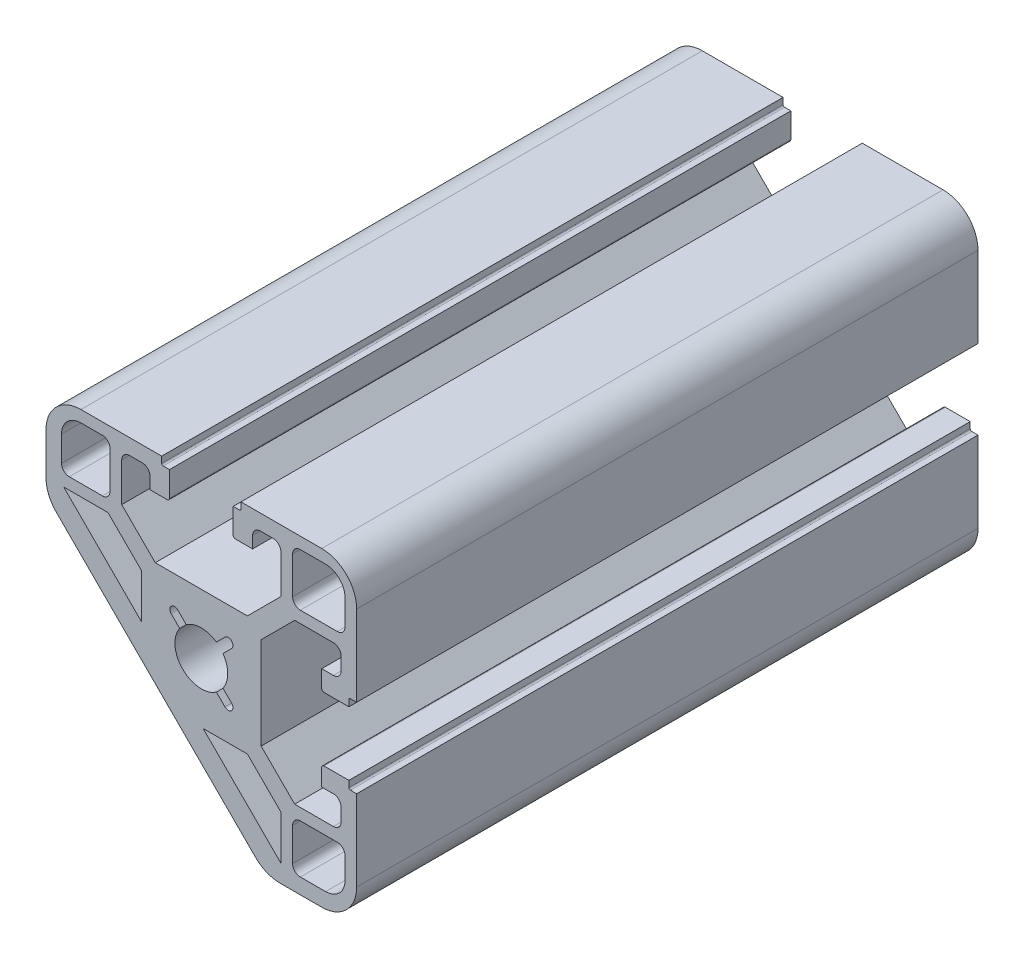
SolidWorks part; units mm, degrees
ref_plane "前视基准面" through (0, 0, 0) normal (0, 0, 1) x (1, 0, 0)
ref_plane "上视基准面" through (0, 0, 0) normal (0, 1, 0) x (1, 0, 0)
ref_plane "右视基准面" through (0, 0, 0) normal (1, 0, 0) x (0, 0, -1)
sketch "草图1" plane through (0, 0, 0) normal (0, 0, 1) x (1, 0, 0)
  line L0 (2339.1839, 210.4729) -> (2328.7839, 210.4729)
  line L1 (2324.2839, 205.9729) -> (2324.2839, 200.6211)
  line L2 (2325.6019, 197.4392) -> (2351.2501, 171.7909)
  line L3 (2354.4321, 170.4729) -> (2359.7839, 170.4729)
  line L4 (2364.2839, 174.9729) -> (2364.2839, 185.3729)
  line L5 (2337.6839, 205.9729) -> (2337.6839, 207.4729)
  line L6 (2336.6839, 208.4729) -> (2335.0339, 208.4729)
  line L7 (2334.0339, 207.4729) -> (2334.0339, 202.4907)
  line L8 (2340.1839, 209.4729) -> (2339.3839, 209.4729)
  line L9 (2339.1839, 209.6729) -> (2339.1839, 210.4729)
  line L10 (2340.1839, 209.4729) -> (2340.1839, 206.2729)
  line L11 (2339.8839, 205.9729) -> (2337.6839, 205.9729)
  line L12 (2338.3516, 198.1729) -> (2350.2161, 198.1729)
  line L13 (2326.2799, 206.4769) -> (2326.2799, 203.2229)
  line L14 (2327.2799, 202.2229) -> (2331.5339, 202.2229)
  line L15 (2332.5339, 203.2229) -> (2332.5339, 207.9769)
  line L16 (2331.5339, 208.9769) -> (2328.7799, 208.9769)
  line L17 (2344.5108, 182.7729) -> (2350.2161, 182.7729)
  line L18 (2336.5839, 196.4051) -> (2336.5839, 190.6998)
  line L19 (2351.9839, 184.5407) -> (2351.9839, 196.4051)
  line L20 (2350.2161, 198.1729) -> (2338.3516, 198.1729)
  line L21 (2332.2661, 200.7229) -> (2336.5839, 196.4051)
  line L22 (2334.0339, 202.4907) -> (2338.3516, 198.1729)
  line L23 (2349.3839, 210.4729) -> (2359.7839, 210.4729)
  line L24 (2364.2839, 205.9729) -> (2364.2839, 195.5729)
  line L25 (2350.8839, 205.9729) -> (2350.8839, 207.4729)
  line L26 (2351.8839, 208.4729) -> (2353.5339, 208.4729)
  line L27 (2354.5339, 207.4729) -> (2354.5339, 202.4907)
  line L28 (2348.3839, 209.4729) -> (2349.1839, 209.4729)
  line L29 (2349.3839, 209.6729) -> (2349.3839, 210.4729)
  line L30 (2364.2839, 195.5729) -> (2363.4839, 195.5729)
  line L31 (2363.2839, 195.3729) -> (2363.2839, 194.5729)
  line L32 (2359.7839, 197.0729) -> (2359.7839, 194.8729)
  line L33 (2360.0839, 194.5729) -> (2363.2839, 194.5729)
  line L34 (2348.3839, 209.4729) -> (2348.3839, 206.2729)
  line L35 (2348.6839, 205.9729) -> (2350.8839, 205.9729)
  line L36 (2362.7879, 206.4769) -> (2362.7879, 203.2229)
  line L37 (2361.7879, 202.2229) -> (2357.0339, 202.2229)
  line L38 (2356.0339, 203.2229) -> (2356.0339, 207.9769)
  line L39 (2357.0339, 208.9769) -> (2360.2879, 208.9769)
  line L40 (2356.3016, 200.7229) -> (2351.9839, 196.4051)
  line L41 (2354.5339, 202.4907) -> (2350.2161, 198.1729)
  line L42 (2359.7839, 197.0729) -> (2361.2839, 197.0729)
  line L43 (2362.2839, 198.0729) -> (2362.2839, 199.7229)
  line L44 (2361.2839, 200.7229) -> (2356.3016, 200.7229)
  line L45 (2364.2839, 185.3729) -> (2363.4839, 185.3729)
  line L46 (2363.2839, 185.5729) -> (2363.2839, 186.3729)
  line L47 (2359.7839, 183.8729) -> (2359.7839, 186.0729)
  line L48 (2360.0839, 186.3729) -> (2363.2839, 186.3729)
  line L49 (2348.3839, 174.6572) -> (2348.3839, 174.6729)
  line L50 (2362.7879, 174.9689) -> (2362.7879, 177.7229)
  line L51 (2361.7879, 178.7229) -> (2357.0339, 178.7229)
  line L52 (2356.0339, 177.7229) -> (2356.0339, 173.4689)
  line L53 (2357.0339, 172.4689) -> (2360.2879, 172.4689)
  line L54 (2356.3016, 180.2229) -> (2351.9839, 184.5407)
  line L55 (2354.5339, 178.4551) -> (2350.2161, 182.7729)
  line L56 (2359.7839, 183.8729) -> (2361.2839, 183.8729)
  line L57 (2362.2839, 182.8729) -> (2362.2839, 181.2229)
  line L58 (2361.2839, 180.2229) -> (2356.3016, 180.2229)
  line L59 (2326.5608, 200.7229) -> (2336.5839, 190.6998)
  line L60 (2344.5108, 182.7729) -> (2354.5339, 172.7498)
  line L61 (2332.2661, 200.7229) -> (2326.5608, 200.7229)
  line L62 (2354.5339, 178.4551) -> (2354.5339, 172.7498)
  line L63 (2347.3244, 194.362) -> (2346.226, 193.2636)
  line L64 (2348.1729, 193.5135) -> (2347.0746, 192.4151)
  line L65 (2341.2433, 194.362) -> (2342.3417, 193.2636)
  line L66 (2340.3948, 193.5135) -> (2341.4932, 192.4151)
  line L67 (2347.3244, 186.5838) -> (2346.226, 187.6822)
  line L68 (2348.1729, 187.4324) -> (2347.0746, 188.5307)
  arc A0 (2328.7839, 210.4729) -> (2324.2839, 205.9729) centre (2328.7839, 205.9729) ccw
  arc A1 (2324.2839, 200.6211) -> (2325.6019, 197.4392) centre (2328.7839, 200.6211) ccw
  arc A2 (2351.2501, 171.7909) -> (2354.4321, 170.4729) centre (2354.4321, 174.9729) ccw
  arc A3 (2359.7839, 170.4729) -> (2364.2839, 174.9729) centre (2359.7839, 174.9729) ccw
  arc A4 (2337.6839, 207.4729) -> (2336.6839, 208.4729) centre (2336.6839, 207.4729) ccw
  arc A5 (2335.0339, 208.4729) -> (2334.0339, 207.4729) centre (2335.0339, 207.4729) ccw
  arc A6 (2339.1839, 209.6729) -> (2339.3839, 209.4729) centre (2339.3839, 209.6729) ccw
  arc A7 (2339.8839, 205.9729) -> (2340.1839, 206.2729) centre (2339.8839, 206.2729) ccw
  arc A8 (2346.226, 193.2636) -> (2342.3417, 193.2636) centre (2344.2839, 190.4729) ccw
  arc A9 (2341.4932, 192.4151) -> (2346.226, 187.6822) centre (2344.2839, 190.4729) ccw
  arc A10 (2347.0746, 188.5307) -> (2347.0746, 192.4151) centre (2344.2839, 190.4729) ccw
  arc A11 (2326.2799, 203.2229) -> (2327.2799, 202.2229) centre (2327.2799, 203.2229) ccw
  arc A12 (2332.5339, 207.9769) -> (2331.5339, 208.9769) centre (2331.5339, 207.9769) ccw
  arc A13 (2331.5339, 202.2229) -> (2332.5339, 203.2229) centre (2331.5339, 203.2229) ccw
  arc A14 (2328.7799, 208.9769) -> (2326.2799, 206.4769) centre (2328.7799, 206.4769) ccw
  arc A15 (2364.2839, 205.9729) -> (2359.7839, 210.4729) centre (2359.7839, 205.9729) ccw
  arc A16 (2351.8839, 208.4729) -> (2350.8839, 207.4729) centre (2351.8839, 207.4729) ccw
  arc A17 (2354.5339, 207.4729) -> (2353.5339, 208.4729) centre (2353.5339, 207.4729) ccw
  arc A18 (2349.1839, 209.4729) -> (2349.3839, 209.6729) centre (2349.1839, 209.6729) ccw
  arc A19 (2363.4839, 195.5729) -> (2363.2839, 195.3729) centre (2363.4839, 195.3729) ccw
  arc A20 (2359.7839, 194.8729) -> (2360.0839, 194.5729) centre (2360.0839, 194.8729) ccw
  arc A21 (2348.3839, 206.2729) -> (2348.6839, 205.9729) centre (2348.6839, 206.2729) ccw
  arc A22 (2361.7879, 202.2229) -> (2362.7879, 203.2229) centre (2361.7879, 203.2229) ccw
  arc A23 (2357.0339, 208.9769) -> (2356.0339, 207.9769) centre (2357.0339, 207.9769) ccw
  arc A24 (2356.0339, 203.2229) -> (2357.0339, 202.2229) centre (2357.0339, 203.2229) ccw
  arc A25 (2362.7879, 206.4769) -> (2360.2879, 208.9769) centre (2360.2879, 206.4769) ccw
  arc A26 (2361.2839, 197.0729) -> (2362.2839, 198.0729) centre (2361.2839, 198.0729) ccw
  arc A27 (2362.2839, 199.7229) -> (2361.2839, 200.7229) centre (2361.2839, 199.7229) ccw
  arc A28 (2363.2839, 185.5729) -> (2363.4839, 185.3729) centre (2363.4839, 185.5729) ccw
  arc A29 (2360.0839, 186.3729) -> (2359.7839, 186.0729) centre (2360.0839, 186.0729) ccw
  arc A30 (2362.7879, 177.7229) -> (2361.7879, 178.7229) centre (2361.7879, 177.7229) ccw
  arc A31 (2356.0339, 173.4689) -> (2357.0339, 172.4689) centre (2357.0339, 173.4689) ccw
  arc A32 (2357.0339, 178.7229) -> (2356.0339, 177.7229) centre (2357.0339, 177.7229) ccw
  arc A33 (2360.2879, 172.4689) -> (2362.7879, 174.9689) centre (2360.2879, 174.9689) ccw
  arc A34 (2362.2839, 182.8729) -> (2361.2839, 183.8729) centre (2361.2839, 182.8729) ccw
  arc A35 (2361.2839, 180.2229) -> (2362.2839, 181.2229) centre (2361.2839, 181.2229) ccw
  arc A36 (2348.1729, 193.5135) -> (2347.3244, 194.362) centre (2347.7487, 193.9377) ccw
  arc A37 (2341.2433, 194.362) -> (2340.3948, 193.5135) centre (2340.819, 193.9377) ccw
  arc A38 (2347.3244, 186.5838) -> (2348.1729, 187.4324) centre (2347.7487, 187.0081) ccw
extrude "凸台-拉伸1" add sketch "草图1" along normal blind 80
